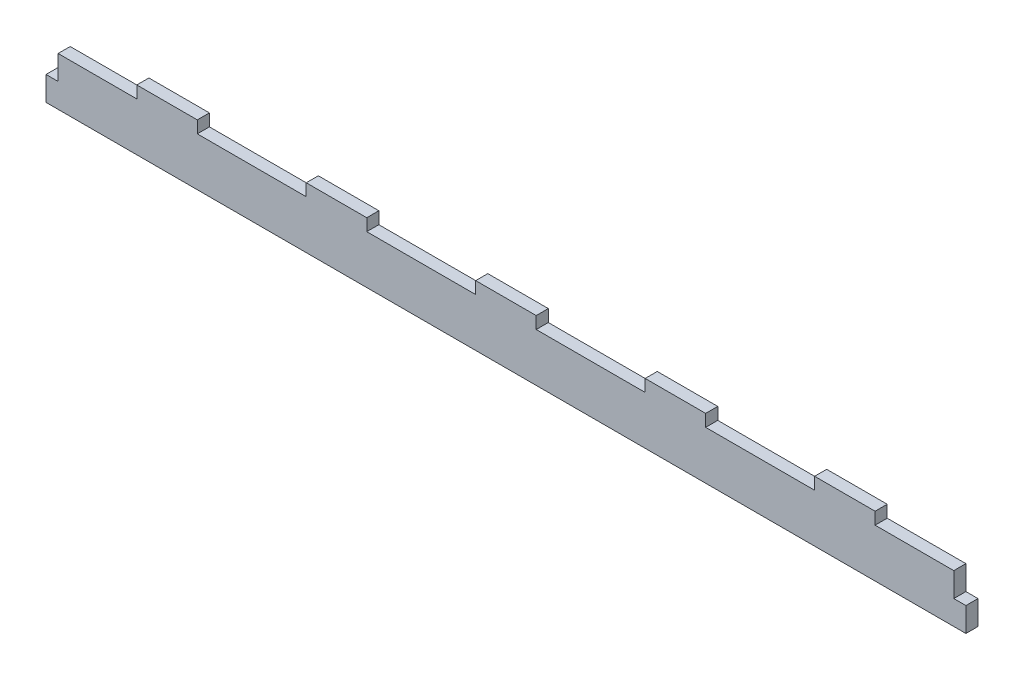
SolidWorks part; units mm, degrees
ref_plane "Front Plane" through (0, 0, 0) normal (0, 0, 1) x (1, 0, 0)
ref_plane "Top Plane" through (0, 0, 0) normal (0, 1, 0) x (1, 0, 0)
ref_plane "Right Plane" through (0, 0, 0) normal (1, 0, 0) x (0, 0, -1)
sketch "Sketch1" plane through (0, 0, 0) normal (0, 0, 1) x (1, 0, 0)
  line L1 (410, -25) -> (377.5, -25)
  line L2 (410, -25) -> (410, -35)
  line L3 (410, -45) -> (40, -45)
  line L4 (40, -25) -> (40, -35)
  line L5 (410, -45) -> (415, -45)
  line L7 (410, -35) -> (415, -35)
  line L8 (415, -45) -> (415, -35)
  line L9 (410, -45) -> (415, -35) construction
  line L10 (225, -65) -> (225, -81.6334) construction
  line L11 (212.5, -25) -> (167.5, -25)
  line L13 (212.5, -25) -> (212.5, -20)
  line L14 (212.5, -20) -> (237.5, -20)
  line L15 (237.5, -25) -> (237.5, -20)
  line L16 (225, -25) -> (237.5, -20) construction
  line L17 (212.5, -20) -> (225, -25) construction
  line L19 (35, -45) -> (35, -35)
  line L20 (40, -35) -> (35, -35)
  line L21 (40, -45) -> (35, -45)
  line L23 (167.5, -25) -> (167.5, -20)
  line L24 (142.5, -20) -> (167.5, -20)
  line L25 (142.5, -25) -> (142.5, -20)
  line L26 (97.5, -25) -> (97.5, -20)
  line L27 (72.5, -20) -> (97.5, -20)
  line L28 (72.5, -25) -> (72.5, -20)
  line L29 (237.5, -25) -> (237.5, -20)
  line L30 (212.5, -20) -> (237.5, -20)
  line L31 (212.5, -25) -> (212.5, -20)
  line L32 (167.5, -25) -> (167.5, -20)
  line L33 (142.5, -20) -> (167.5, -20)
  line L34 (142.5, -25) -> (142.5, -20)
  line L35 (307.5, -25) -> (307.5, -20)
  line L36 (282.5, -20) -> (307.5, -20)
  line L37 (282.5, -25) -> (282.5, -20)
  line L38 (237.5, -25) -> (237.5, -20)
  line L39 (212.5, -20) -> (237.5, -20)
  line L40 (212.5, -25) -> (212.5, -20)
  line L41 (307.5, -25) -> (307.5, -20)
  line L42 (282.5, -20) -> (307.5, -20)
  line L43 (282.5, -25) -> (282.5, -20)
  line L44 (377.5, -25) -> (377.5, -20)
  line L45 (352.5, -20) -> (377.5, -20)
  line L46 (352.5, -25) -> (352.5, -20)
  line L47 (352.5, -25) -> (307.5, -25)
  line L48 (282.5, -25) -> (237.5, -25)
  line L49 (142.5, -25) -> (97.5, -25)
  line L50 (72.5, -25) -> (40, -25)
  point P4 (410, -45)
  point P11 (225, -25)
  point P16 (40, -46.458)
  point P23 (40, -45)
  point P24 (410, -50)
  point P25 (0, 0)
  point P26 (0, 0)
  point P40 (40, -49.5163)
  dimension "D1" = 20
  dimension "D2" = 3
  dimension "D3" = 5
  dimension "D4" = 10
  dimension "D5" = 25
  dimension "D6" = 5
  dimension "D7" = 3
extrude "Boss-Extrude1" add sketch "Sketch1" along normal mid plane 5
